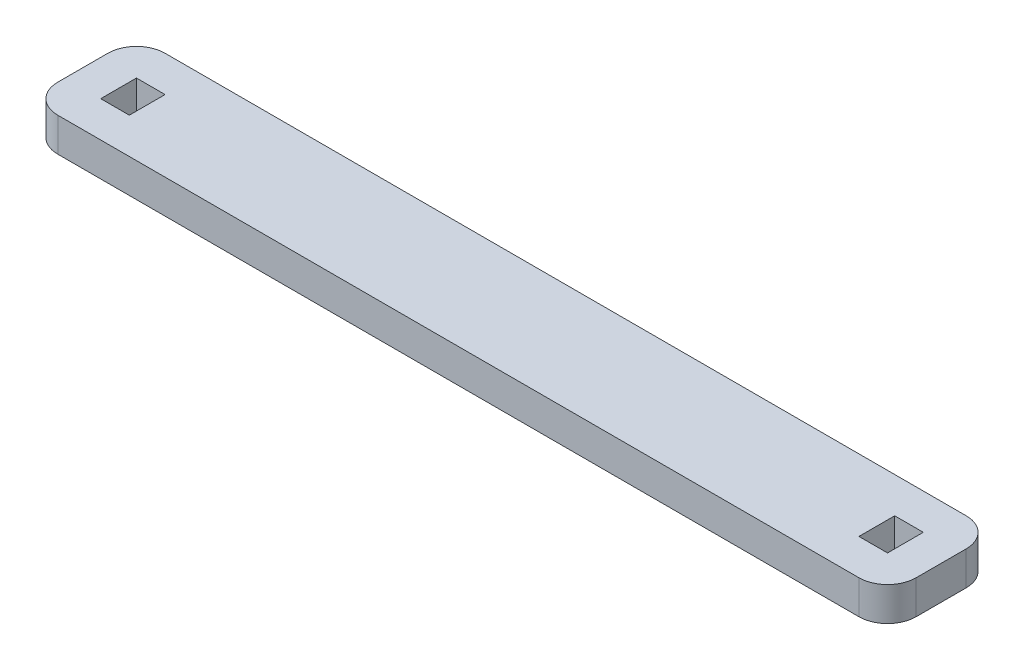
SolidWorks part; units mm, degrees
ref_plane "Front Plane" through (0, 0, 0) normal (0, 0, 1) x (1, 0, 0)
ref_plane "Top Plane" through (0, 0, 0) normal (0, 1, 0) x (1, 0, 0)
ref_plane "Right Plane" through (0, 0, 0) normal (1, 0, 0) x (0, 0, -1)
sketch "Sketch1" plane through (0, 0, 0) normal (0, 1, 0) x (1, 0, 0)
  line L0 (-33.655, 0) -> (33.655, 0) construction
  line L6 (38.1, -4.7625) -> (-38.1, -4.7625)
  line L7 (-32.385, -1.5875) -> (-34.925, -1.5875)
  line L8 (-32.385, -1.5875) -> (-32.385, 1.5875)
  line L9 (-32.385, 1.5875) -> (-34.925, 1.5875)
  line L10 (-34.925, -1.5875) -> (-34.925, 1.5875)
  line L11 (-32.385, -1.5875) -> (-34.925, 1.5875) construction
  line L12 (-32.385, 1.5875) -> (-34.925, -1.5875) construction
  line L13 (34.925, -1.5875) -> (32.385, -1.5875)
  line L14 (34.925, -1.5875) -> (34.925, 1.5875)
  line L15 (34.925, 1.5875) -> (32.385, 1.5875)
  line L16 (32.385, -1.5875) -> (32.385, 1.5875)
  line L17 (34.925, -1.5875) -> (32.385, 1.5875) construction
  line L18 (34.925, 1.5875) -> (32.385, -1.5875) construction
  line L19 (38.1, -4.7625) -> (38.1, 4.7625)
  line L20 (38.1, 4.7625) -> (-38.1, 4.7625)
  line L21 (-38.1, -4.7625) -> (-38.1, 4.7625)
  line L22 (38.1, -4.7625) -> (-38.1, 4.7625) construction
  line L23 (38.1, 4.7625) -> (-38.1, -4.7625) construction
  point P0 (0, 0)
  point P1 (0, 0)
  point P6 (-33.655, 0)
  point P11 (33.655, 0)
  dimension "D1" = 9.525
  dimension "D2" = 3.175
  dimension "D3" = 2.54
  dimension "D4" = 67.31
  dimension "D5" = 3.175
extrude "Boss-Extrude1" add sketch "Sketch1" along normal mid plane 3
fillet "Fillet1" radius 2.54 4 edges at (-38.1, 0, -4.7625) (38.1, 0, -4.7625) (38.1, 0, 4.7625) (-38.1, 0, 4.7625)
